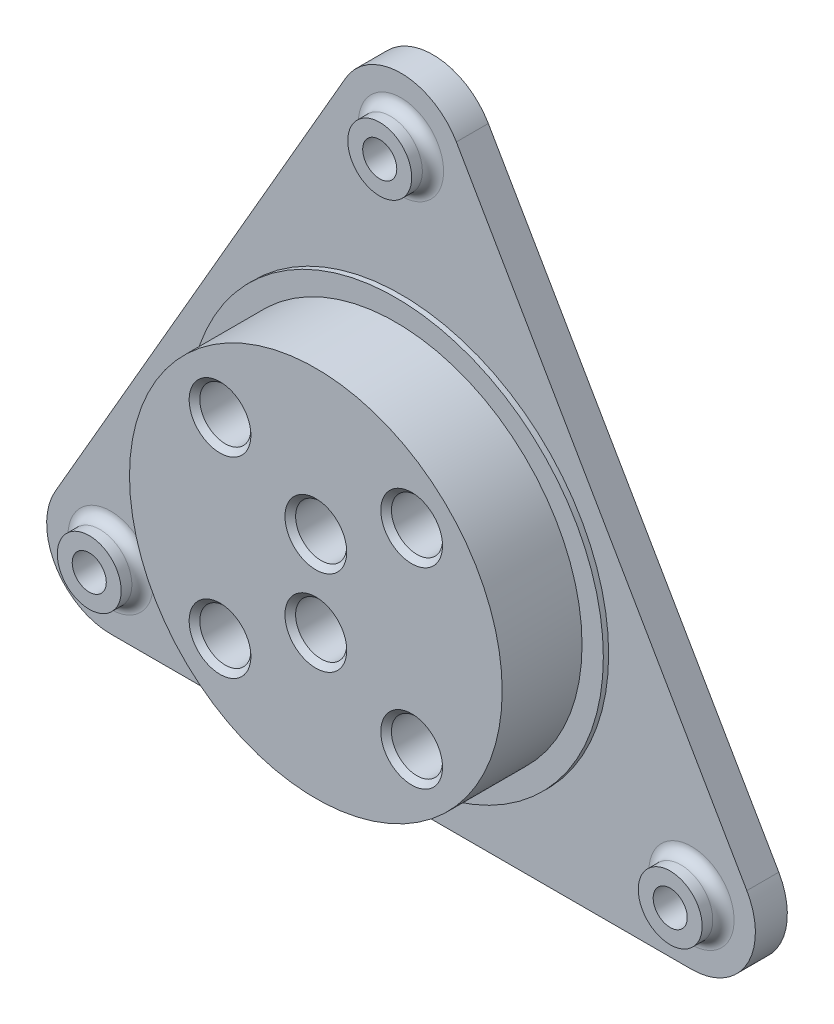
SolidWorks part; units mm, degrees
ref_plane "Front Plane" through (0, 0, 0) normal (0, 0, 1) x (1, 0, 0)
ref_plane "Top Plane" through (0, 0, 0) normal (0, 1, 0) x (1, 0, 0)
ref_plane "Right Plane" through (0, 0, 0) normal (1, 0, 0) x (0, 0, -1)
sketch "Sketch1" plane through (0, 0, 0) normal (1, 0, 0) x (0, 0, -1)
  line L0 (0, 0) -> (0, 45)
  line L1 (0, 45) -> (-3, 45)
  line L2 (-3, 45) -> (-3, 19.5)
  line L3 (-3.5, 17.5) -> (-11, 17.5)
  line L4 (-11, 17.5) -> (-11, 0)
  line L5 (-11, 0) -> (0, 0)
  line L6 (0, 0) -> (-73.6158, 0) construction
  line L7 (-3.5, 17.5) -> (-3.5, 19.5)
  line L8 (-3.5, 19.5) -> (-3, 19.5)
  dimension "D1" = 35
  dimension "D2" = 90
  dimension "D3" = 3
  dimension "D4" = 8
  dimension "D5" = 0.5
  dimension "D6" = 2
revolve "Revolve1" add sketch "Sketch1" angle 360 about L5
sketch "Sketch2" plane through (0, 0, 0) normal (0, 0, -1) x (-1, 0, 0)
  circle A0 centre (0, 0) radius 31.5 construction
  circle A1 centre (0, 31.5) radius 1.6
  circle A2 centre (27.2798, -15.75) radius 1.6
  circle A3 centre (-27.2798, -15.75) radius 1.6
  point P11 (0, 0)
  dimension "D1" = 63
  dimension "D3" = 3.2
  dimension "D2" = 3
extrude "Cut-Extrude1" cut sketch "Sketch2" against normal through all
sketch "Sketch3" plane through (0, 0, 11) normal (0, 0, 1) x (1, 0, 0)
  line L0 (0, -4) -> (0, 4) construction
  line L2 (9, -9) -> (-9, -9) construction
  line L3 (9, -9) -> (9, 9) construction
  line L4 (9, 9) -> (-9, 9) construction
  line L5 (-9, -9) -> (-9, 9) construction
  line L6 (9, -9) -> (-9, 9) construction
  line L7 (9, 9) -> (-9, -9) construction
  circle A0 centre (0, 4) radius 2.4
  circle A1 centre (0, -4) radius 2.4
  circle A2 centre (-9, 9) radius 2.4
  circle A3 centre (9, 9) radius 2.4
  circle A4 centre (9, -9) radius 2.4
  circle A5 centre (-9, -9) radius 2.4
  point P0 (0, 0)
  point P10 (0, 0)
  dimension "D1" = 4.8
  dimension "D3" = 4.8
  dimension "8" = 8
  dimension "D4" = 18
extrude "Cut-Extrude2" cut sketch "Sketch3" against normal blind 4
sketch "Sketch5" plane through (0, 0, 3) normal (0, 0, -1) x (-1, 0, 0)
  line L0 (-5.1962, 34.5) -> (-32.476, -12.75)
  line L6 (5.1962, 34.5) -> (32.476, -12.75)
  line L7 (-27.2798, -21.75) -> (27.2798, -21.75)
  arc A0 (5.1962, 34.5) -> (-5.1962, 34.5) centre (0, 31.5) ccw
  arc A1 (-32.476, -12.75) -> (-27.2798, -21.75) centre (-27.2798, -15.75) ccw
  arc A2 (27.2798, -21.75) -> (32.476, -12.75) centre (27.2798, -15.75) ccw
  circle A3 centre (0, 0) radius 17.5 construction
  circle A4 centre (0, 0) radius 17.5 construction
  dimension "D1" = 12
extrude "Cut-Extrude4" cut sketch "Sketch5" along normal through all flip side to cut
chamfer "Chamfer1" distance 0.5 angle 45 6 edges at (2.4, -4, 11) (2.4, 4, 11) (-6.6, -9, 11) (11.4, -9, 11) (11.4, 9, 11) (-6.6, 9, 11)
sketch "Sketch6" plane through (0, 0, 3) normal (0, 0, 1) x (1, 0, 0)
  circle A0 centre (-27.2798, -15.75) radius 1.6 construction
  circle A1 centre (27.2798, -15.75) radius 1.6 construction
  circle A2 centre (0, 31.5) radius 1.6 construction
  circle A3 centre (-27.2798, -15.75) radius 1.6
  circle A4 centre (27.2798, -15.75) radius 1.6
  circle A5 centre (0, 31.5) radius 1.6
  circle A6 centre (0, 31.5) radius 3
  circle A7 centre (-27.2798, -15.75) radius 3
  circle A8 centre (27.2798, -15.75) radius 3
  dimension "D1" = 6
extrude "Boss-Extrude1" add sketch "Sketch6" along normal blind 2
fillet "Fillet1" radius 1 3 edges at (-30.2798, -15.75, 3) (24.2798, -15.75, 3) (-3, 31.5, 3)
sketch "Sketch7" plane through (0, 0, 11) normal (0, 0, 1) x (1, 0, 0)
  circle A0 centre (-9, 9) radius 1.75
  circle A1 centre (0, 4) radius 1.75
  circle A2 centre (9, 9) radius 1.75
  circle A3 centre (9, -9) radius 1.75
  circle A4 centre (-9, -9) radius 1.75
  circle A5 centre (0, -4) radius 1.75
  dimension "D1" = 3.5
extrude "Cut-Extrude5" cut sketch "Sketch7" against normal blind 6
equation "\"D1@Sketch1\" = \"Bearing ID@Motor Bearing<1>.Part\""
equation "\"D1@Sketch2\" = ( \"Sun Teeth Num@Drive Module.Assembly\" + \"Planet Teeth Num@Drive Module.Assembly\" ) * \"Module@Drive Module.Assembly\""
